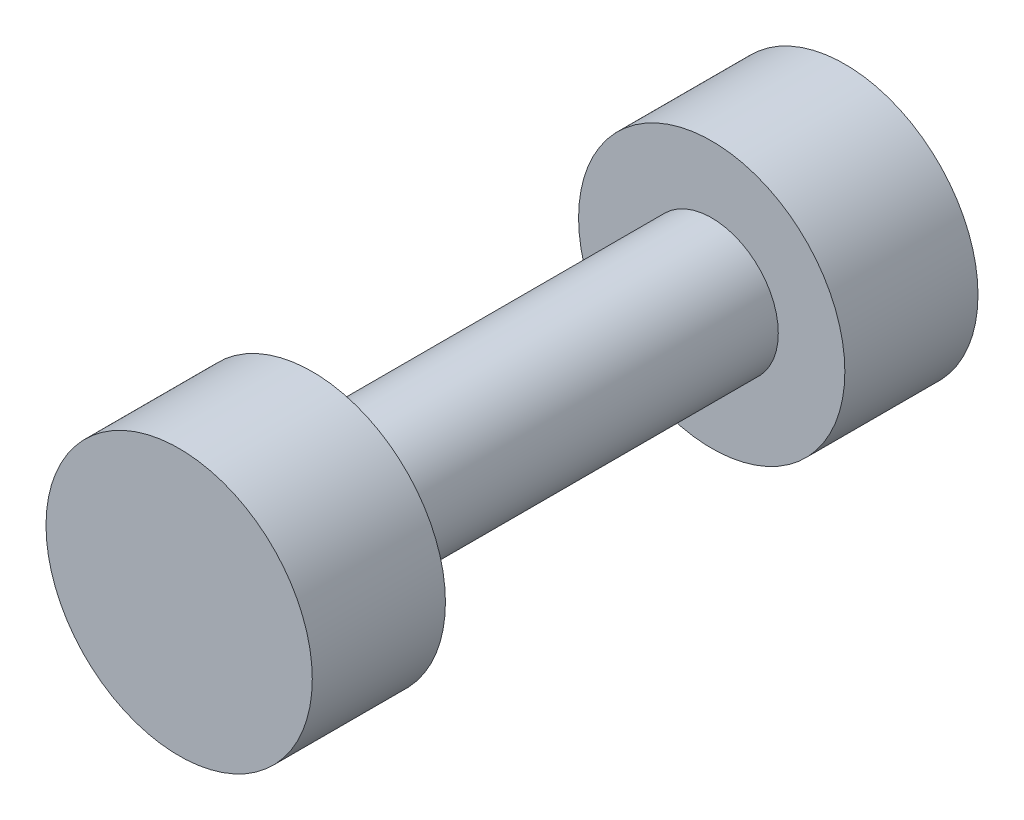
SolidWorks part; units mm, degrees
ref_plane "Front Plane" through (0, 0, 0) normal (0, 0, 1) x (1, 0, 0)
ref_plane "Top Plane" through (0, 0, 0) normal (0, 1, 0) x (1, 0, 0)
ref_plane "Right Plane" through (0, 0, 0) normal (1, 0, 0) x (0, 0, -1)
sketch "Sketch1" plane through (0, 0, 0) normal (0, 0, 1) x (1, 0, 0)
  circle A0 centre (0, 0) radius 0.5
  dimension "D1" = 1
extrude "Boss-Extrude1" add sketch "Sketch1" along normal mid plane 3
sketch "Sketch2" plane through (0, 0, 1.5) normal (0, 0, 1) x (1, 0, 0)
  circle A0 centre (0, 0) radius 1
  dimension "D1" = 2
extrude "Boss-Extrude2" add sketch "Sketch2" along normal blind 1
mirror "Mirror1" about plane through (0, 0, 0) normal (0, 0, 1) of "Boss-Extrude2"
